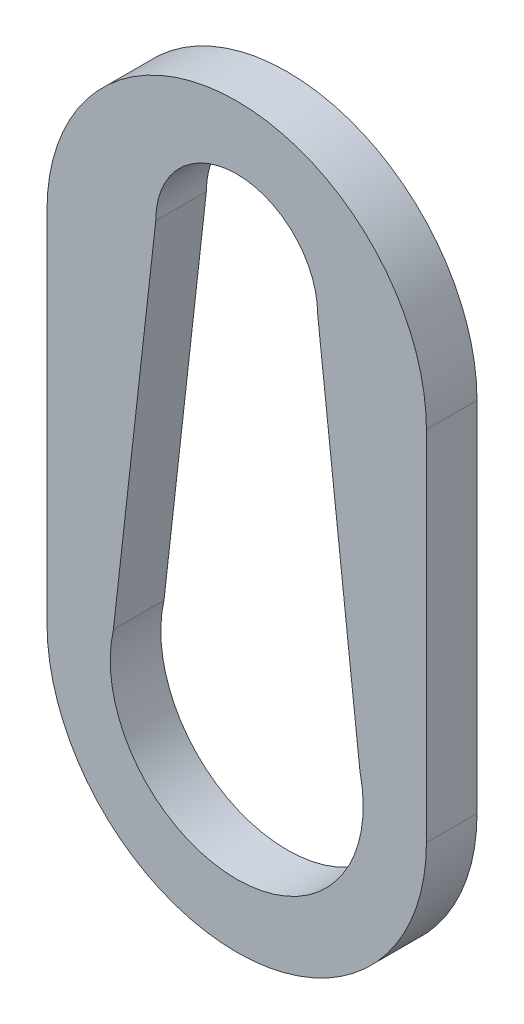
SolidWorks part; units mm, degrees
ref_plane "Front Plane" through (0, 0, 0) normal (0, 0, 1) x (1, 0, 0)
ref_plane "Top Plane" through (0, 0, 0) normal (0, 1, 0) x (1, 0, 0)
ref_plane "Right Plane" through (0, 0, 0) normal (1, 0, 0) x (0, 0, -1)
sketch "Sketch1" plane through (0, 0, 0) normal (0, 0, 1) x (1, 0, 0)
  line L3 (73.0854, 59.9315) -> (73.0854, 74.0776)
  line L5 (88.0854, 59.9315) -> (88.0854, 74.0776)
  line L6 (77.3854, 75.8776) -> (75.5854, 59.9315)
  line L7 (83.7854, 75.8776) -> (85.5854, 59.9315)
  arc A0 (73.0854, 74.0776) -> (88.0854, 74.0776) centre (80.5854, 74.0776) cw
  arc A1 (73.0854, 59.9315) -> (88.0854, 59.9315) centre (80.5854, 59.9315) ccw
  circle A2 centre (80.5854, 74.0776) radius 0.1664
  circle A3 centre (80.5854, 59.9315) radius 1.85
  circle A7 centre (80.5854, 59.9315) radius 5
  circle A8 centre (80.5854, 75.8776) radius 3.2
  point P4 (80.5854, 81.5776)
  point P6 (77.3854, 75.3776)
  point P8 (83.7854, 75.3776)
  point P21 (80.5854, 79.0776)
  point P23 (77.3854, 75.8776)
  point P26 (83.7854, 75.8776)
  point P27 (76.4765, 62.7804)
  point P28 (84.6944, 62.7804)
  point P29 (80.5854, 56.0529)
  point P30 (80.5854, 74.2441)
  dimension "D3" = 10
  dimension "D1" = 14.1462
  dimension "D2" = 15
  dimension "D4" = 2.5
extrude "Boss-Extrude1" add sketch "Sketch1" along normal blind 2
